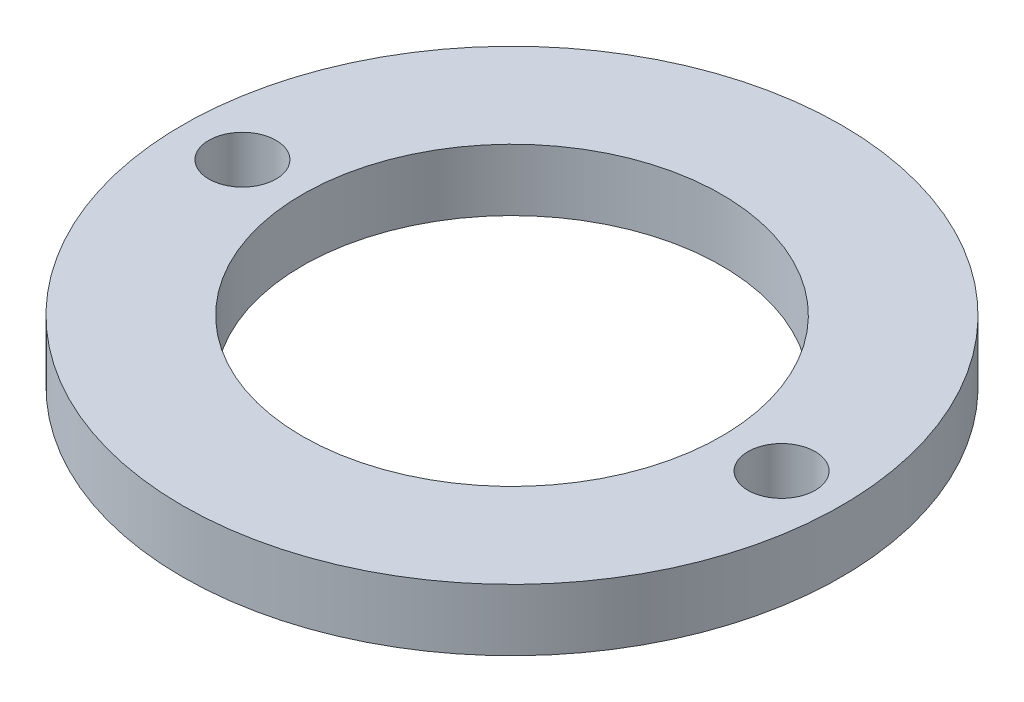
SolidWorks part; units mm, degrees
material "Acrylic (Medium-high impact)"
ref_plane "Front Plane" through (0, 0, 0) normal (0, 0, 1) x (1, 0, 0)
ref_plane "Top Plane" through (0, 0, 0) normal (0, 1, 0) x (1, 0, 0)
ref_plane "Right Plane" through (0, 0, 0) normal (1, 0, 0) x (0, 0, -1)
sketch "Sketch1" plane through (0, 0, 0) normal (0, 1, 0) x (1, 0, 0)
  circle A0 centre (0, 0) radius 16
  circle A1 centre (0, 0) radius 10.175
  dimension "D1" = 32
  dimension "D2" = 20.35
extrude "Boss-Extrude1" add sketch "Sketch1" along normal blind 3
hole_wizard "#4 Clearance Hole1" positions "Sketch6" profile "Sketch3" hole size "#4" standard "ANSI Inch" end condition through all
sketch "Sketch6" plane through (0, 3, 0) normal (0, 1, 0) x (1, 0, 0)
  point P0 (-13.0875, 0)
  point P2 (13.0875, 0)
  dimension "D2" = 13.0875
  dimension "D4" = 13.0875
sketch "Sketch3" plane through (-13.0875, 3, 0) normal (1, 0, 0) x (0, 0, 1)
  line L0 (0, 0) -> (0, 3)
  line L1 (0, 3) -> (1.6319, 3)
  line L2 (1.6319, 3) -> (1.6319, 0)
  line L5 (1.6319, 0) -> (0, 0)
  line L11 (0, -6.35) -> (0, 107.95) construction
  dimension "Thru Hole Dia." = 3.2639
  dimension "Thru Hole Depth" = 3
equation "\"D4@Sketch6\"=\"D2@Sketch6\""
